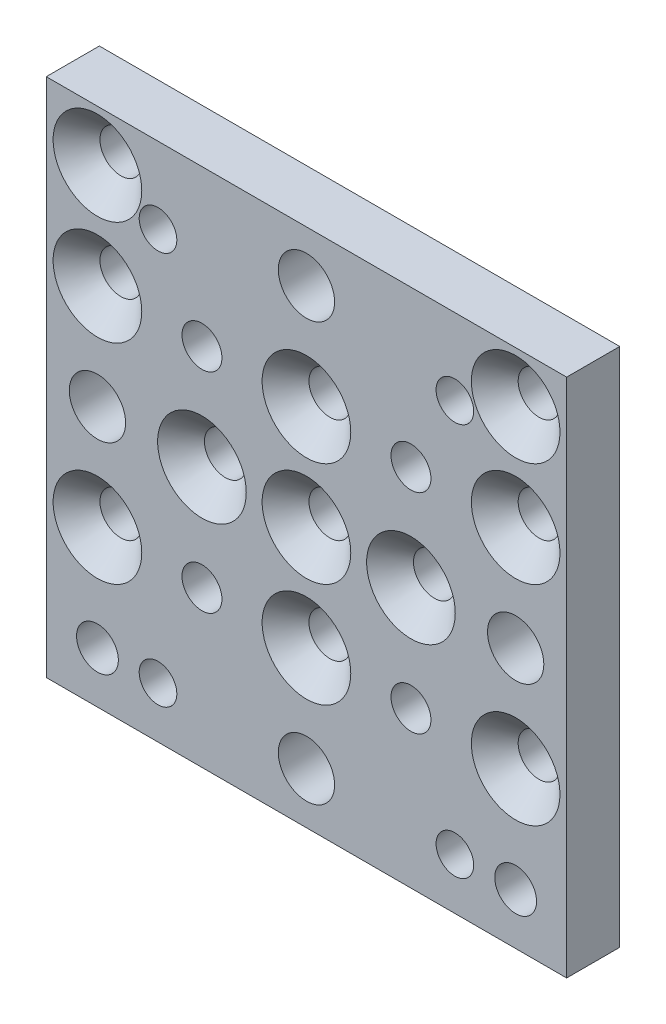
SolidWorks part; units mm, degrees
ref_plane "Front Plane" through (0, 0, 0) normal (0, 0, 1) x (1, 0, 0)
ref_plane "Top Plane" through (0, 0, 0) normal (0, 1, 0) x (1, 0, 0)
ref_plane "Right Plane" through (0, 0, 0) normal (1, 0, 0) x (0, 0, -1)
sketch "Sketch1" plane through (0, 0, 0) normal (0, 0, 1) x (1, 0, 0)
  line L4 (31.115, 31.115) -> (-31.115, 31.115)
  line L5 (-31.115, 31.115) -> (-31.115, -31.115)
  line L6 (-31.115, -31.115) -> (31.115, -31.115)
  line L7 (31.115, -31.115) -> (31.115, 31.115)
  line L8 (31.115, 31.115) -> (-31.115, 31.115)
  line L9 (-31.115, 31.115) -> (-31.115, -31.115)
  line L10 (-31.115, -31.115) -> (31.115, -31.115)
  line L11 (31.115, -31.115) -> (31.115, 31.115)
  circle A0 centre (25.019, 25.0063) radius 2.5 construction
  circle A1 centre (25.019, 12.4968) radius 2.5 construction
  circle A2 centre (25.019, -12.4968) radius 2.5 construction
  circle A3 centre (25.019, -24.9936) radius 2.5 construction
  circle A4 centre (12.4968, -24.9936) radius 2.5 construction
  circle A5 centre (12.4968, 0) radius 2.5 construction
  circle A6 centre (12.4968, 25.0063) radius 2.5 construction
  circle A7 centre (0, 12.4968) radius 2.5 construction
  circle A8 centre (0, 0) radius 2.5 construction
  circle A9 centre (0, -12.4968) radius 2.5 construction
  circle A10 centre (-12.4968, -24.9936) radius 2.5 construction
  circle A11 centre (-24.9936, -24.9936) radius 2.5 construction
  circle A12 centre (-24.9936, -12.4968) radius 2.5 construction
  circle A13 centre (-12.4968, 0) radius 2.5 construction
  circle A14 centre (-12.4968, 25.0063) radius 2.5 construction
  circle A15 centre (-24.9936, 25.0063) radius 2.5 construction
  circle A16 centre (-24.9936, 12.4968) radius 2.5 construction
  circle A17 centre (25.019, 25.0063) radius 2.5
  circle A18 centre (25.019, 12.4968) radius 2.5
  circle A19 centre (25.019, -12.4968) radius 2.5
  circle A20 centre (25.019, -24.9936) radius 2.5
  circle A21 centre (12.4968, -24.9936) radius 2.5 construction
  circle A22 centre (12.4968, 0) radius 2.5
  circle A23 centre (12.4968, 25.0063) radius 2.5 construction
  circle A24 centre (0, 12.4968) radius 2.5
  circle A25 centre (0, 0) radius 2.5
  circle A26 centre (0, -12.4968) radius 2.5
  circle A27 centre (-12.4968, -24.9936) radius 2.5 construction
  circle A28 centre (-24.9936, -24.9936) radius 2.5
  circle A29 centre (-24.9936, -12.4968) radius 2.5
  circle A30 centre (-12.4968, 0) radius 2.5
  circle A31 centre (-12.4968, 25.0063) radius 2.5 construction
  circle A32 centre (-24.9936, 25.0063) radius 2.5
  circle A33 centre (-24.9936, 12.4968) radius 2.5
  circle A34 centre (-17.75, 22) radius 2.25 construction
  circle A35 centre (17.75, 22) radius 2.25 construction
  circle A36 centre (17.75, -25) radius 2.25 construction
  circle A37 centre (-17.75, -25) radius 2.25 construction
  circle A38 centre (-17.75, 22) radius 2.25
  circle A39 centre (17.75, 22) radius 2.25
  circle A40 centre (17.75, -25) radius 2.25
  circle A41 centre (-17.75, -25) radius 2.25
  dimension "D1" = 0
extrude "Boss-Extrude1" add sketch "Sketch1" along normal blind 6.35
chamfer "Chamfer1" distance 2.8 angle 45 11 edges at (27.519, 25.0063, 6.35) (27.519, 12.4968, 6.35) (27.519, -12.4968, 6.35) (-22.4936, -12.4968, 6.35) (-22.4936, 12.4968, 6.35) (-22.4936, 25.0063, 6.35) (2.5, 12.4968, 6.35) (-9.9968, 0, 6.35) (14.9968, 0, 6.35) (2.5, 0, 6.35) (2.5, -12.4968, 6.35)
sketch "Sketch2" plane through (0, 0, 6.35) normal (0, 0, 1) x (1, 0, 0)
  circle A0 centre (0, -24.9936) radius 3.3655 construction
  circle A1 centre (0, 25.019) radius 3.3655 construction
  circle A2 centre (12.4968, 12.4968) radius 2.3876 construction
  circle A3 centre (-12.4968, 12.4968) radius 2.3876 construction
  circle A4 centre (-12.4968, -12.4968) radius 2.3876 construction
  circle A5 centre (12.4968, -12.4968) radius 2.3876 construction
  circle A6 centre (25.019, 0) radius 3.3655 construction
  circle A7 centre (-24.9936, 0) radius 3.3655 construction
  circle A8 centre (0, -24.9936) radius 3.3655
  circle A9 centre (0, 25.019) radius 3.3655
  circle A10 centre (12.4968, 12.4968) radius 2.3876
  circle A11 centre (-12.4968, 12.4968) radius 2.3876
  circle A12 centre (-12.4968, -12.4968) radius 2.3876
  circle A13 centre (12.4968, -12.4968) radius 2.3876
  circle A14 centre (25.019, 0) radius 3.3655
  circle A15 centre (-24.9936, 0) radius 3.3655
extrude "Cut-Extrude2" cut sketch "Sketch2" against normal through all
